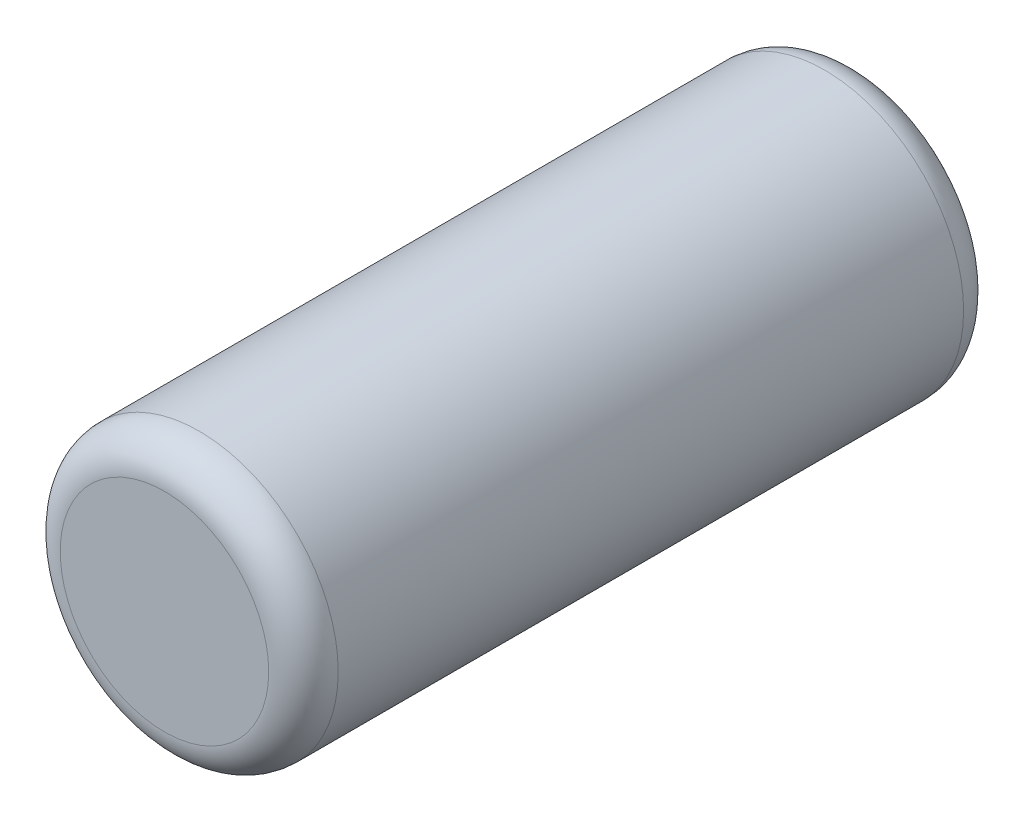
SolidWorks part; units mm, degrees
ref_plane "Plan de face" through (0, 0, 0) normal (0, 0, 1) x (1, 0, 0)
ref_plane "Plan de dessus" through (0, 0, 0) normal (0, 1, 0) x (1, 0, 0)
ref_plane "Plan de droite" through (0, 0, 0) normal (1, 0, 0) x (0, 0, -1)
sketch "Esquisse1" plane through (0, 0, 0) normal (0, 0, 1) x (1, 0, 0)
  circle A0 centre (0, 0) radius 4
  dimension "D1" = 8
extrude "Boss.-Extru.1" add sketch "Esquisse1" along normal blind 20
fillet "Congé1" radius 1 2 edges at (4, 0, 0) (4, 0, 20)
